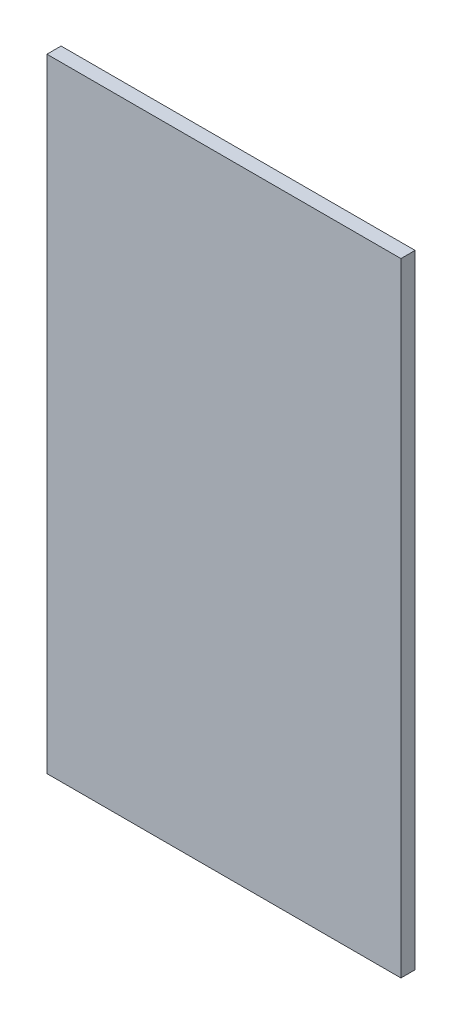
SolidWorks part; units mm, degrees
material "PET"
ref_plane "Front Plane" through (0, 0, 0) normal (0, 0, 1) x (1, 0, 0)
ref_plane "Top Plane" through (0, 0, 0) normal (0, 1, 0) x (1, 0, 0)
ref_plane "Right Plane" through (0, 0, 0) normal (1, 0, 0) x (0, 0, -1)
sketch "Sketch1" plane through (0, 0, 0) normal (0, 0, 1) x (1, 0, 0)
  line L1 (-28.5714, 241.1048) -> (121.4286, 241.1048)
  line L2 (-28.5714, 241.1048) -> (-28.5714, -22.8952)
  line L3 (-28.5714, -22.8952) -> (121.4286, -22.8952)
  line L4 (121.4286, 241.1048) -> (121.4286, -22.8952)
  dimension "D1" = 264
  dimension "D2" = 150
extrude "Boss-Extrude1" add sketch "Sketch1" along normal blind 6
